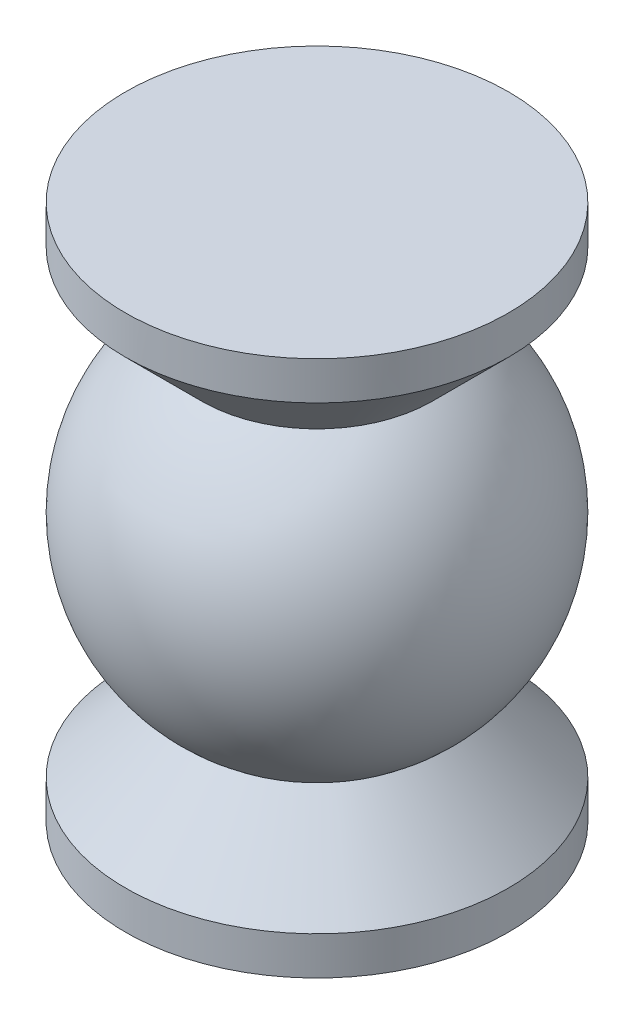
SolidWorks part; units mm, degrees
ref_plane "前视基准面" through (0, 0, 0) normal (0, 0, 1) x (1, 0, 0)
ref_plane "上视基准面" through (0, 0, 0) normal (0, 1, 0) x (1, 0, 0)
ref_plane "右视基准面" through (0, 0, 0) normal (1, 0, 0) x (0, 0, -1)
sketch "草图1" plane through (0, 0, 0) normal (0, 0, 1) x (1, 0, 0)
  line L0 (0, 0) -> (0, 23.8608) construction
  line L1 (0, 0) -> (25, 0)
  line L2 (25, 0) -> (25, 5)
  line L3 (25, 5) -> (15, 15)
  line L4 (15, 55) -> (25, 65)
  line L5 (25, 65) -> (25, 70)
  line L6 (25, 70) -> (0, 70)
  line L7 (0, 0) -> (0, 70)
  arc A0 (15, 15) -> (15, 55) centre (0, 35) ccw
  dimension "D1" = 5
  dimension "D5" = 25
  dimension "D2" = 5
  dimension "D3" = 40
  dimension "D4" = 70
  dimension "D6" = 35
  dimension "D7" = 25
revolve "旋转1" add sketch "草图1" angle 360 about L0
